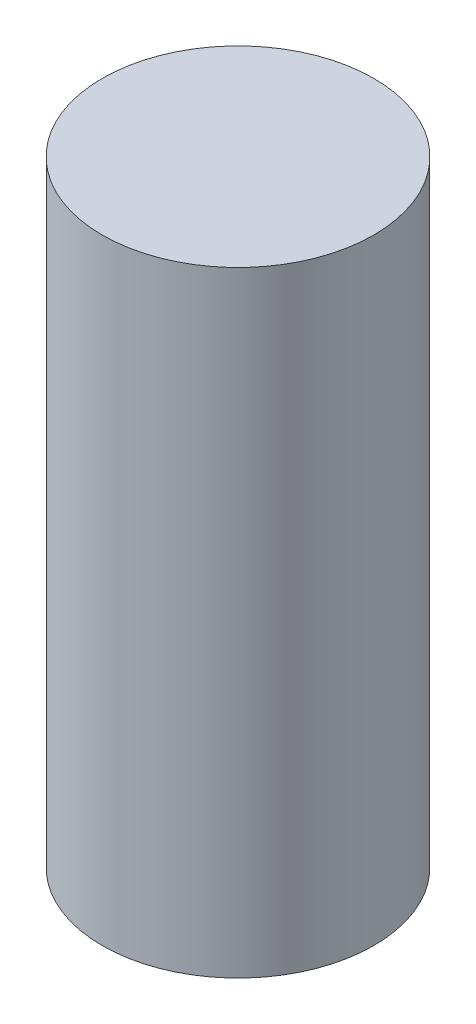
SolidWorks part; units mm, degrees
ref_plane "Front Plane" through (0, 0, 0) normal (0, 0, 1) x (1, 0, 0)
ref_plane "Top Plane" through (0, 0, 0) normal (0, 1, 0) x (1, 0, 0)
ref_plane "Right Plane" through (0, 0, 0) normal (1, 0, 0) x (0, 0, -1)
sketch "Sketch3" plane through (0, 0, 0) normal (0, 1, 0) x (1, 0, 0)
  circle A0 centre (0, 0) radius 1.985
  dimension "D1" = 3.97
extrude "Boss-Extrude1" add sketch "Sketch3" along normal blind 9
